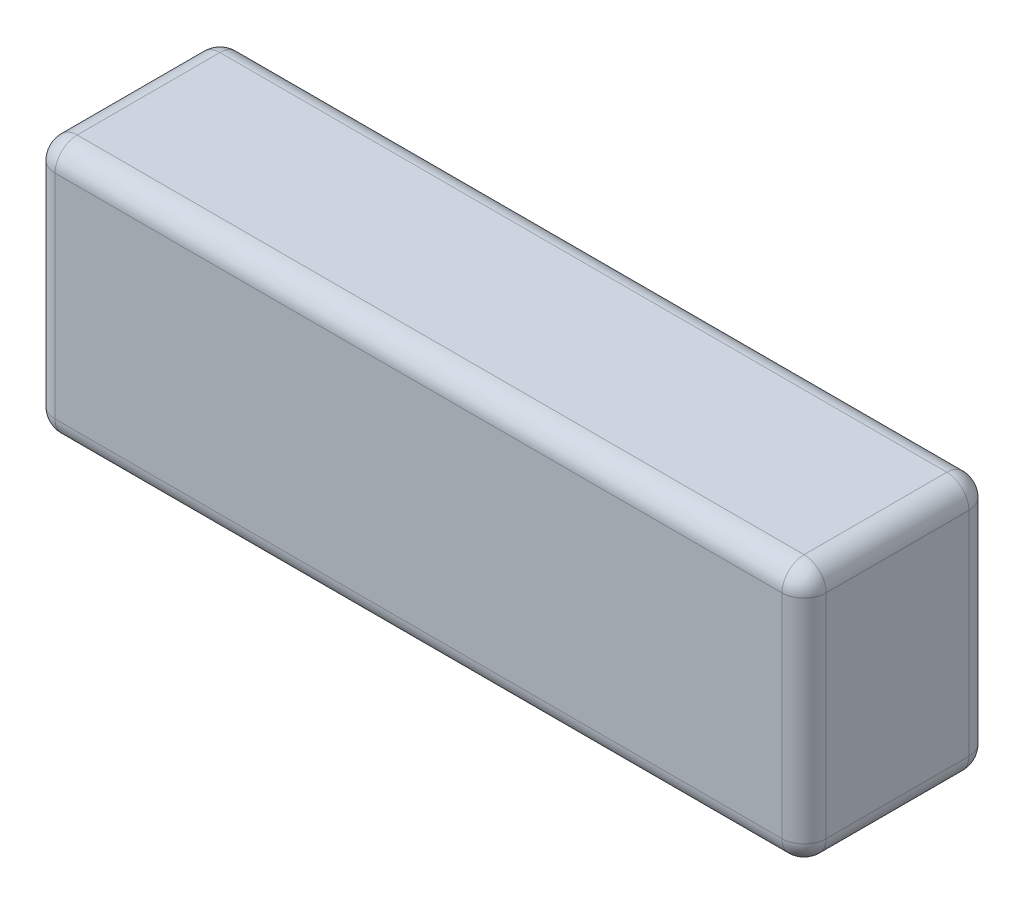
SolidWorks part; units mm, degrees
ref_plane "Alzado" through (0, 0, 0) normal (0, 0, 1) x (1, 0, 0)
ref_plane "Planta" through (0, 0, 0) normal (0, 1, 0) x (1, 0, 0)
ref_plane "Vista lateral" through (0, 0, 0) normal (1, 0, 0) x (0, 0, -1)
sketch "Croquis1" plane through (0, 0, 0) normal (0, 0, 1) x (1, 0, 0)
  line L0 (55, 0) -> (-55, 0) construction
  line L1 (-49.3875, 17.4625) -> (49.3875, 17.4625)
  line L2 (-52.3875, 14.4625) -> (-52.3875, -14.4625)
  line L3 (-49.3875, -17.4625) -> (49.3875, -17.4625)
  line L4 (52.3875, 14.4625) -> (52.3875, -14.4625)
  line L5 (0, -55) -> (0, 55) construction
  arc A0 (49.3875, 17.4625) -> (52.3875, 14.4625) centre (49.3875, 14.4625) cw
  arc A1 (49.3875, -17.4625) -> (52.3875, -14.4625) centre (49.3875, -14.4625) ccw
  arc A2 (-52.3875, -14.4625) -> (-49.3875, -17.4625) centre (-49.3875, -14.4625) ccw
  arc A3 (-49.3875, 17.4625) -> (-52.3875, 14.4625) centre (-49.3875, 14.4625) ccw
  point P4 (0, 17.4625)
  point P5 (-52.3875, 0)
  point P14 (52.3875, -17.4625)
  point P17 (-52.3875, -17.4625)
  point P20 (-52.3875, 17.4625)
  dimension "D3" = 3
  dimension "D1" = 104.775
  dimension "D2" = 34.925
extrude "Saliente-Extruir1" add sketch "Croquis1" along normal mid plane 25.4
fillet "Redondeo1" radius 3 8 edges at (-51.5088, 16.5838, 12.7) (-52.3875, 0, 12.7) (-51.5088, -16.5838, 12.7) (0, -17.4625, 12.7) (51.5088, -16.5838, 12.7) (52.3875, 0, 12.7) (51.5088, 16.5838, 12.7) (0, 17.4625, 12.7)
fillet "Redondeo2" radius 3 8 edges at (0, 17.4625, -12.7) (51.5088, 16.5838, -12.7) (52.3875, 0, -12.7) (51.5088, -16.5838, -12.7) (0, -17.4625, -12.7) (-51.5088, -16.5838, -12.7) (-52.3875, 0, -12.7) (-51.5088, 16.5838, -12.7)
